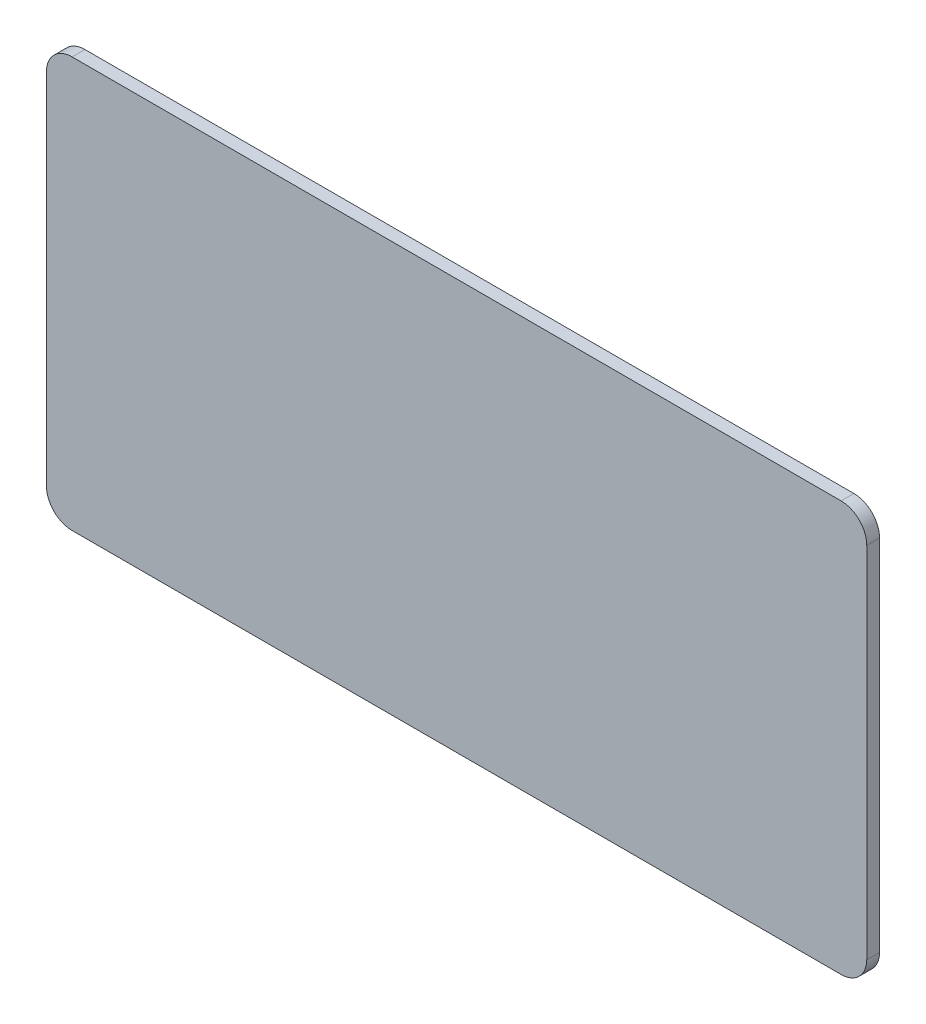
SolidWorks part; units mm, degrees
material "Стекло кварцевое прозрачное"
ref_plane "Спереди" through (0, 0, 0) normal (0, 0, 1) x (1, 0, 0)
ref_plane "Сверху" through (0, 0, 0) normal (0, 1, 0) x (1, 0, 0)
ref_plane "Справа" through (0, 0, 0) normal (1, 0, 0) x (0, 0, -1)
sketch "Sketch3" plane through (0, 0, 0) normal (0, 0, 1) x (1, 0, 0)
  line L4 (-160, 0) -> (160, 0) construction
  line L12 (0, 80) -> (0, -80) construction
  line L13 (-150, 80) -> (150, 80)
  line L14 (-160, 70) -> (-160, -70)
  line L15 (-150, -80) -> (150, -80)
  line L24 (160, 70) -> (160, -70)
  line L25 (-160, 80) -> (160, -80) construction
  line L26 (-160, -80) -> (160, 80) construction
  arc A12 (150, -80) -> (160, -70) centre (150, -70) ccw
  arc A13 (150, 80) -> (160, 70) centre (150, 70) cw
  arc A14 (-160, -70) -> (-150, -80) centre (-150, -70) ccw
  arc A15 (-150, 80) -> (-160, 70) centre (-150, 70) ccw
  point P0 (0, 0)
  dimension "D4" = 10
  dimension "D2" = 320
  dimension "D3" = 160
extrude "Boss-Extrude2" add sketch "Sketch3" against normal blind 5
